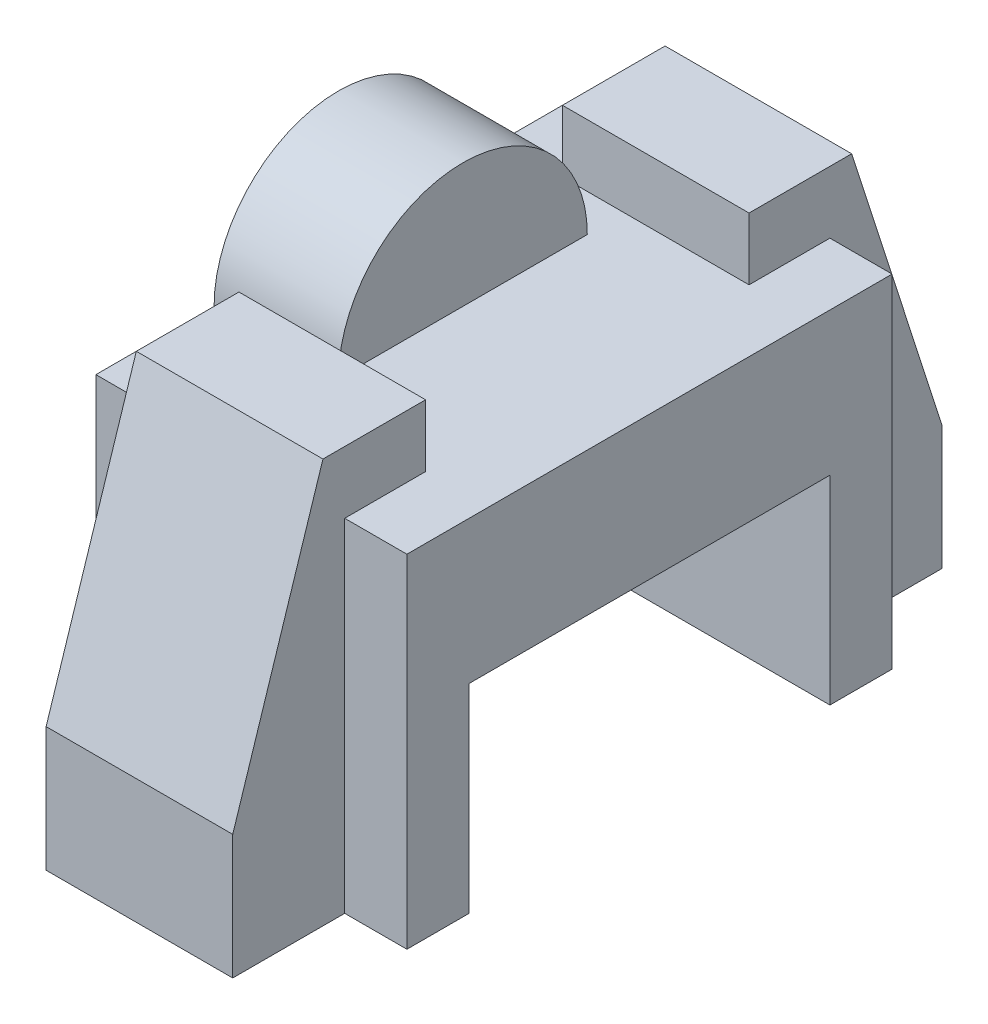
SolidWorks part; units mm, degrees
ref_plane "Alzado" through (0, 0, 0) normal (0, 0, 1) x (1, 0, 0)
ref_plane "Planta" through (0, 0, 0) normal (0, 1, 0) x (1, 0, 0)
ref_plane "Vista lateral" through (0, 0, 0) normal (1, 0, 0) x (0, 0, -1)
sketch "Croquis1" plane through (0, 0, 0) normal (1, 0, 0) x (0, 0, -1)
  line L0 (29, -27.5) -> (39, -27.5)
  line L1 (-39, 27.5) -> (39, 27.5)
  line L2 (-39, 27.5) -> (-39, -27.5)
  line L3 (-39, -27.5) -> (-29, -27.5)
  line L4 (39, 27.5) -> (39, -27.5)
  line L6 (-29, -27.5) -> (-29, 4.5)
  line L7 (-29, 4.5) -> (29, 4.5)
  line L8 (29, -27.5) -> (29, 4.5)
  point P8 (0, 4.5)
  point P9 (39, 0)
  dimension "D1" = 32
  dimension "D2" = 58
  dimension "D3" = 78
  dimension "D4" = 55
extrude "Saliente-Extruir1" add sketch "Croquis1" along normal mid plane 50
sketch "Croquis2" plane through (0, 0, 0) normal (1, 0, 0) x (0, 0, -1)
  line L0 (0, 42.7733) -> (0, -28.2944) construction
  line L1 (-26, 27.5) -> (-26, 37.5)
  line L2 (39, 27.5) -> (-39, 27.5) construction
  line L3 (-26, 37.5) -> (-42.5, 37.5)
  line L4 (-42.5, 37.5) -> (-57, -7.5)
  line L5 (-57, -7.5) -> (-57, -27.5)
  line L6 (-57, -27.5) -> (-39, -27.5)
  line L7 (-39, -27.5) -> (-39, 27.5)
  line L8 (-39, 27.5) -> (-26, 27.5)
  line L9 (39, -27.5) -> (39, 27.5)
  line L10 (57, -27.5) -> (39, -27.5)
  line L11 (57, -7.5) -> (57, -27.5)
  line L12 (42.5, 37.5) -> (57, -7.5)
  line L13 (26, 37.5) -> (42.5, 37.5)
  line L14 (26, 27.5) -> (26, 37.5)
  line L15 (39, 27.5) -> (26, 27.5)
  point P7 (-27.1007, 37.5)
  point P22 (57, 1.2411)
  point P23 (0, 42.7733)
  dimension "D1" = 65
  dimension "D2" = 18
  dimension "D3" = 13
  dimension "D4" = 85
  dimension "D5" = 20
extrude "Saliente-Extruir2" add sketch "Croquis2" along normal mid plane 30
sketch "Croquis3" plane through (0, 0, 0) normal (1, 0, 0) x (0, 0, -1)
  line L0 (39, 27.5) -> (-39, 27.5) construction
  line L1 (-20, 27.5) -> (20, 27.5)
  arc A0 (20, 27.5) -> (-20, 27.5) centre (0, 27.5) ccw
  dimension "D1" = 20
extrude "Saliente-Extruir3" add sketch "Croquis3" along normal blind 20 from surface at -25 starting at face at (-25, -5.75, 0)
